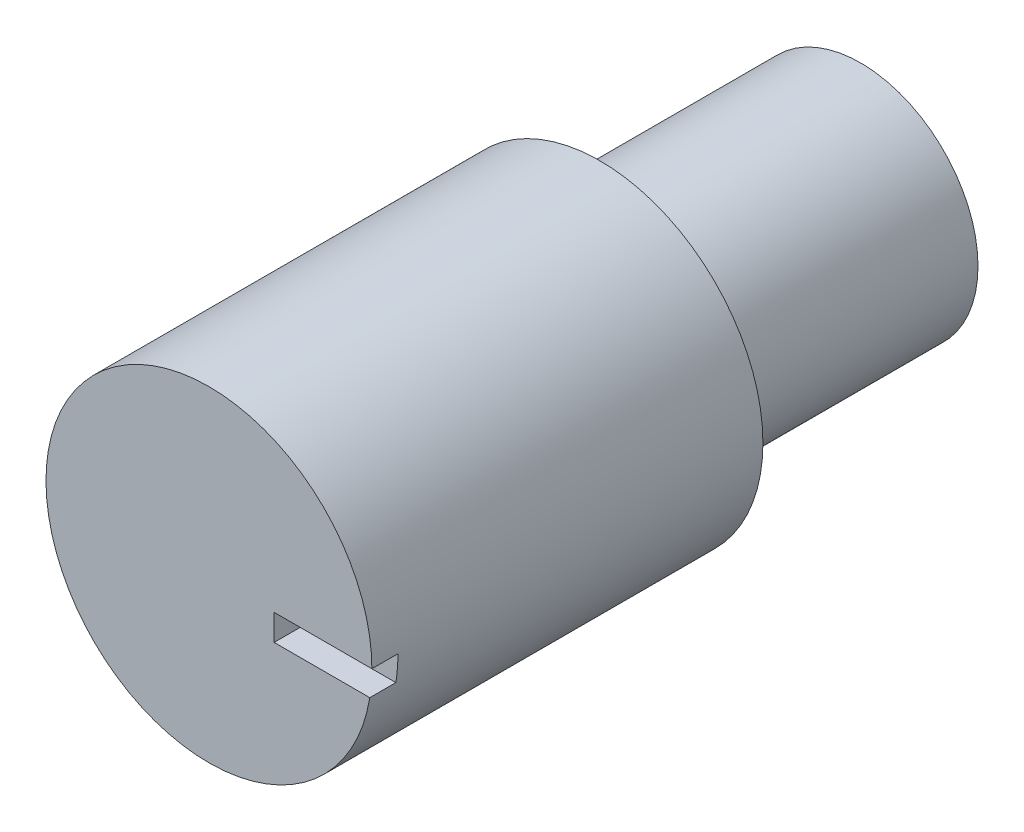
SolidWorks part; units mm, degrees
ref_plane "前视基准面" through (0, 0, 0) normal (0, 0, 1) x (1, 0, 0)
ref_plane "上视基准面" through (0, 0, 0) normal (0, 1, 0) x (1, 0, 0)
ref_plane "右视基准面" through (0, 0, 0) normal (1, 0, 0) x (0, 0, -1)
other "Configuration Table"
sketch "草图1" plane through (0, 0, 0) normal (0, 0, 1) x (1, 0, 0)
  circle A0 centre (0, 0) radius 25
extrude "凸台-拉伸1" add sketch "草图1" against normal blind 60
sketch "草图2" plane through (0, 0, 0) normal (0, 0, 1) x (1, 0, 0)
  circle A0 centre (0, 0) radius 18
extrude "凸台-拉伸2" add sketch "草图2" against normal blind 100
sketch "草图3" plane through (0, 0, 0) normal (0, 1, 0) x (1, 0, 0)
  line L1 (10, -4) -> (35, -4)
  line L2 (10, -4) -> (10, 4)
  line L3 (10, 4) -> (35, 4)
  line L4 (35, -4) -> (35, 4)
extrude "切除-拉伸1" cut sketch "草图3" against normal blind 4
